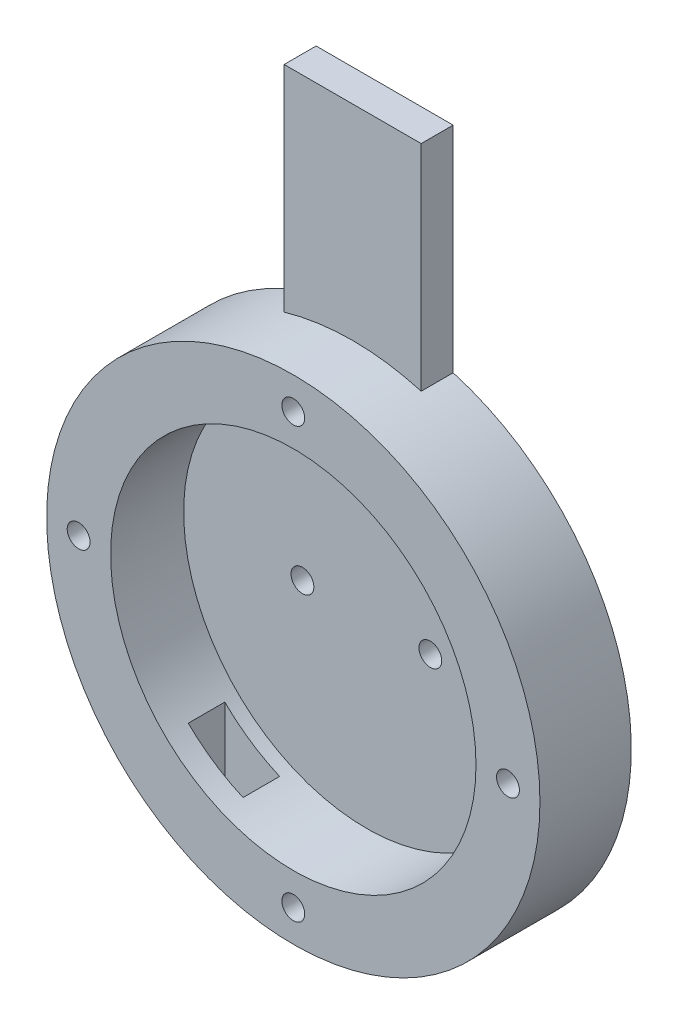
SolidWorks part; units mm, degrees
ref_plane "Front Plane" through (0, 0, 0) normal (0, 0, 1) x (1, 0, 0)
ref_plane "Top Plane" through (0, 0, 0) normal (0, 1, 0) x (1, 0, 0)
ref_plane "Right Plane" through (0, 0, 0) normal (1, 0, 0) x (0, 0, -1)
sketch "Sketch1" plane through (0, 0, 0) normal (0, 0, 1) x (1, 0, 0)
  circle A0 centre (0, 0) radius 27
  circle A1 centre (0, 0) radius 23.5 construction
  circle A2 centre (0, 23.5) radius 1.25
  circle A3 centre (23.5, 0) radius 1.25
  circle A4 centre (0, -23.5) radius 1.25
  circle A5 centre (-23.5, 0) radius 1.25
  circle A6 centre (0, 0) radius 20
  point P15 (0, 0)
  dimension "D1" = 54
  dimension "D2" = 47
  dimension "D3" = 2.5
  dimension "D5" = 40
  dimension "D4" = 4
extrude "Boss-Extrude1" add sketch "Sketch1" along normal blind 10
sketch "Sketch3" plane through (0, 0, 0) normal (0, 0, 1) x (1, 0, 0)
  circle A0 centre (0, 0) radius 20
  circle A1 centre (0, 0) radius 7 construction
  circle A2 centre (-7, 0) radius 1.25
  circle A3 centre (7, 0) radius 1.25
  circle A4 centre (0, 0) radius 11.5 construction
  dimension "D1" = 40
  dimension "D2" = 14
  dimension "D3" = 2.5
  dimension "D4" = 23
extrude "Boss-Extrude2" add sketch "Sketch3" along normal blind 2
sketch "Sketch5" plane through (0, 0, 0) normal (0, 0, 1) x (1, 0, 0)
  line L0 (0, -5.5) -> (0, 5.5) construction
  line L1 (-7.5, 25.248) -> (7.5, 25.248)
  line L2 (-7.5, 25.248) -> (-7.5, 49.4145)
  line L3 (-7.5, 49.4145) -> (7.5, 49.4145)
  line L4 (7.5, 25.248) -> (7.5, 49.4145)
  dimension "D1" = 7.5
  dimension "D2" = 15
extrude "Boss-Extrude3" add sketch "Sketch5" along normal blind 3.5
sketch "Sketch4" plane through (0, 0, 0) normal (0, 1, 0) x (1, 0, 0)
  line L0 (27, -10) -> (-27, -10) construction
  line L1 (-14, -3.5) -> (-8, -3.5)
  line L2 (-14, -3.5) -> (-14, -7.5)
  line L3 (-14, -7.5) -> (-8, -7.5)
  line L4 (-8, -3.5) -> (-8, -7.5)
  line L5 (0, -5.5) -> (0, 5.5) construction
  dimension "D1" = 4
  dimension "D2" = 6
  dimension "D3" = 2.5
  dimension "D4" = 8
extrude "Cut-Extrude1" cut sketch "Sketch4" against normal up to surface (25.7876 mm away)
